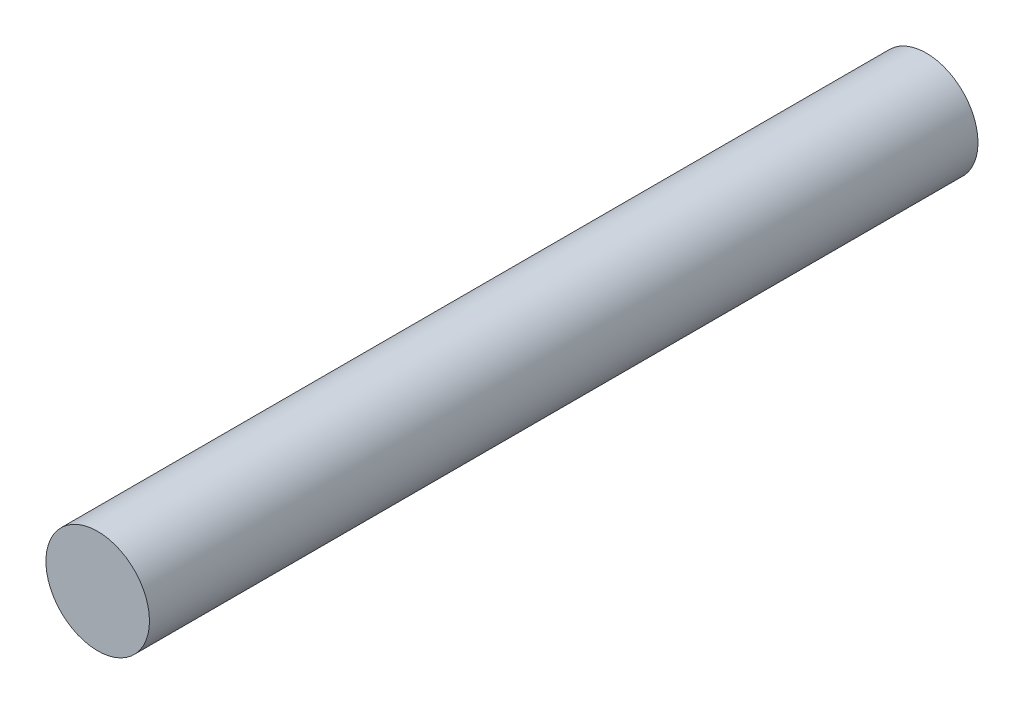
SolidWorks part; units mm, degrees
material "ASTM A36 Steel"
ref_plane "Front Plane" through (0, 0, 0) normal (0, 0, 1) x (1, 0, 0)
ref_plane "Top Plane" through (0, 0, 0) normal (0, 1, 0) x (1, 0, 0)
ref_plane "Right Plane" through (0, 0, 0) normal (1, 0, 0) x (0, 0, -1)
sketch "Sketch3" plane through (0, 0, 0) normal (0, 0, 1) x (1, 0, 0)
  circle A0 centre (0, 0) radius 0.85
  dimension "D1" = 1.7
extrude "Boss-Extrude1" add sketch "Sketch3" along normal blind 13.6
